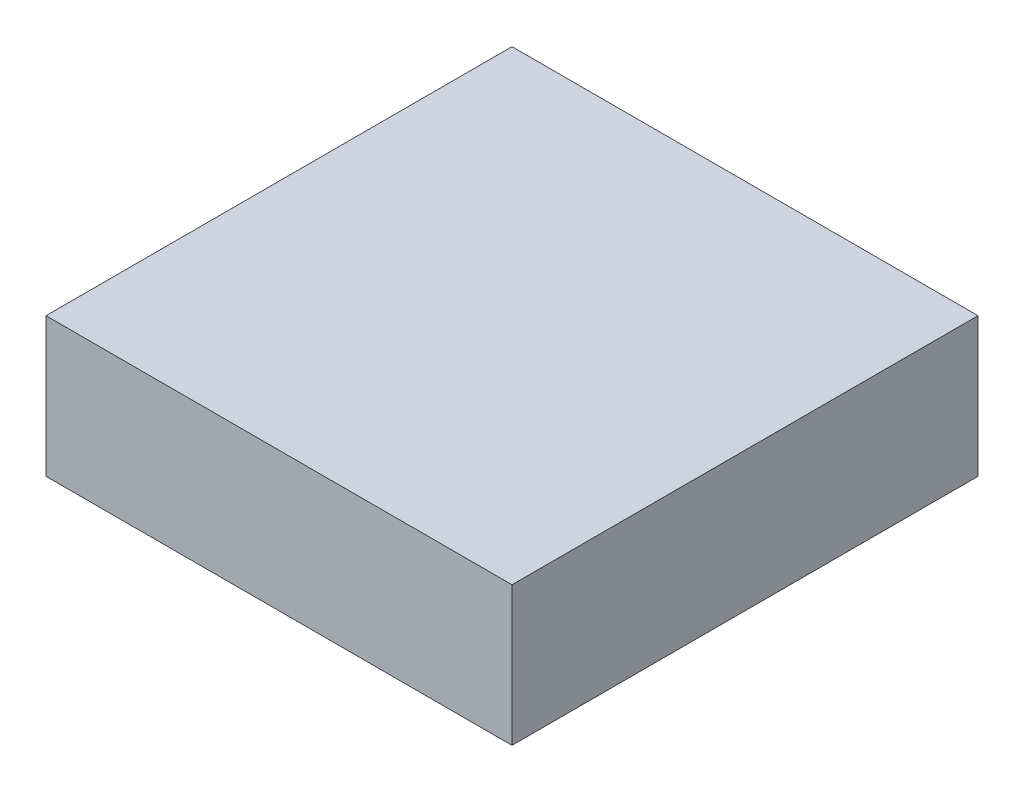
SolidWorks part; units mm, degrees
ref_plane "Front Plane" through (0, 0, 0) normal (0, 0, 1) x (1, 0, 0)
ref_plane "Top Plane" through (0, 0, 0) normal (0, 1, 0) x (1, 0, 0)
ref_plane "Right Plane" through (0, 0, 0) normal (1, 0, 0) x (0, 0, -1)
sketch "Sketch5" plane through (0, 0, 0) normal (0, 1, 0) x (1, 0, 0)
  line L1 (0, 0) -> (170.18, 0)
  line L2 (0, 0) -> (0, 170.18)
  line L3 (0, 170.18) -> (170.18, 170.18)
  line L4 (170.18, 0) -> (170.18, 170.18)
  dimension "D1" = 170.18
extrude "Boss-Extrude5" add sketch "Sketch5" along normal blind 50.8
